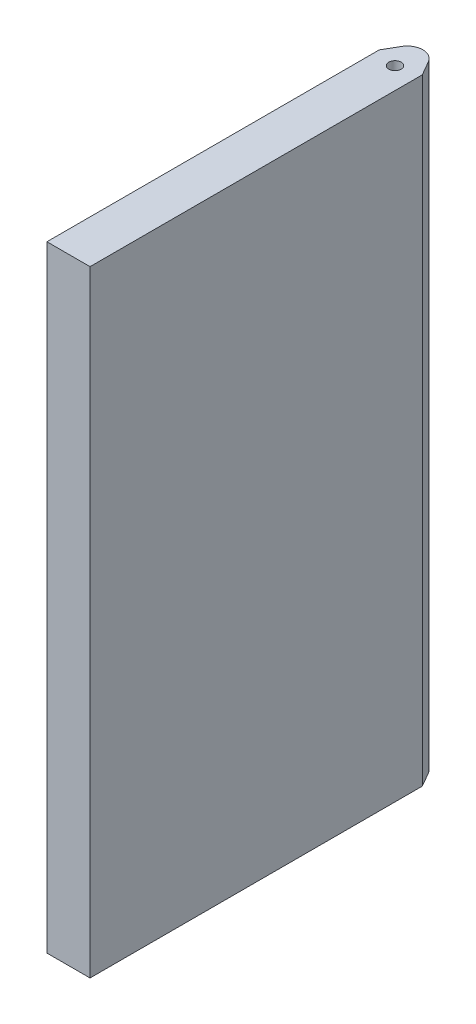
SolidWorks part; units mm, degrees
ref_plane "Front Plane" through (0, 0, 0) normal (0, 0, 1) x (1, 0, 0)
ref_plane "Top Plane" through (0, 0, 0) normal (0, 1, 0) x (1, 0, 0)
ref_plane "Right Plane" through (0, 0, 0) normal (1, 0, 0) x (0, 0, -1)
sketch "Sketch1" plane through (0, 0, 0) normal (0, 1, 0) x (1, 0, 0)
  line L1 (-15, -60) -> (15, -60)
  line L2 (-15, -60) -> (-15, 60)
  line L3 (-15, 60) -> (15, 60)
  line L4 (15, -60) -> (15, 60)
  line L5 (-15, -60) -> (15, 60) construction
  line L6 (-15, 60) -> (15, -60) construction
  point P0 (0, 0)
  dimension "D1" = 30
  dimension "D2" = 120
extrude "Boss-Extrude1" add sketch "Sketch1" along normal blind 200
sketch "Sketch2" plane through (0, 200, 0) normal (0, 1, 0) x (1, 0, 0)
  line L0 (0, 60) -> (-15, 34.0192)
  line L1 (15, 60) -> (-15, 60) construction
  line L2 (-15, 60) -> (-15, -60) construction
  line L3 (-15, 34.0192) -> (-15, -60)
  line L4 (-15, -60) -> (15, -60)
  line L5 (15, -60) -> (15, 34.0192)
  line L6 (15, -60) -> (15, 60) construction
  line L7 (15, 34.0192) -> (0, 60)
  dimension "D1" = 60
  dimension "D2" = 0
extrude "Cut-Extrude2" cut sketch "Sketch2" against normal through all flip side to cut
fillet "Fillet1" radius 5 1 edges at (0, 100, -60)
sketch "Sketch3" plane through (0, 200, 0) normal (0, 1, 0) x (1, 0, 0)
  line L0 (-15, 34.0192) -> (-15, -60)
  line L1 (-15, -60) -> (-7, -60)
  line L2 (-15, -60) -> (15, -60) construction
  line L3 (-7, -60) -> (-7, 47.8756)
  line L4 (-4.3301, 52.5) -> (-15, 34.0192) construction
  line L5 (-7, 47.8756) -> (-15, 34.0192)
  line L6 (7, 47.8756) -> (7, -60)
  line L7 (15, 34.0192) -> (4.3301, 52.5) construction
  line L8 (7, -60) -> (15, -60)
  line L9 (15, -60) -> (15, 34.0192)
  line L10 (15, 34.0192) -> (7, 47.8756)
  dimension "D1" = 8
  dimension "D2" = 8
extrude "Cut-Extrude3" cut sketch "Sketch3" against normal through all
sketch "Sketch4" plane through (0, 0, 0) normal (0, -1, 0) x (1, 0, 0)
  circle A0 centre (0, -46) radius 2
  arc A1 (-4.3301, -52.5) -> (4.3301, -52.5) centre (0, -50) ccw construction
  dimension "D1" = 4
extrude "Cut-Extrude4" cut sketch "Sketch4" against normal through all
